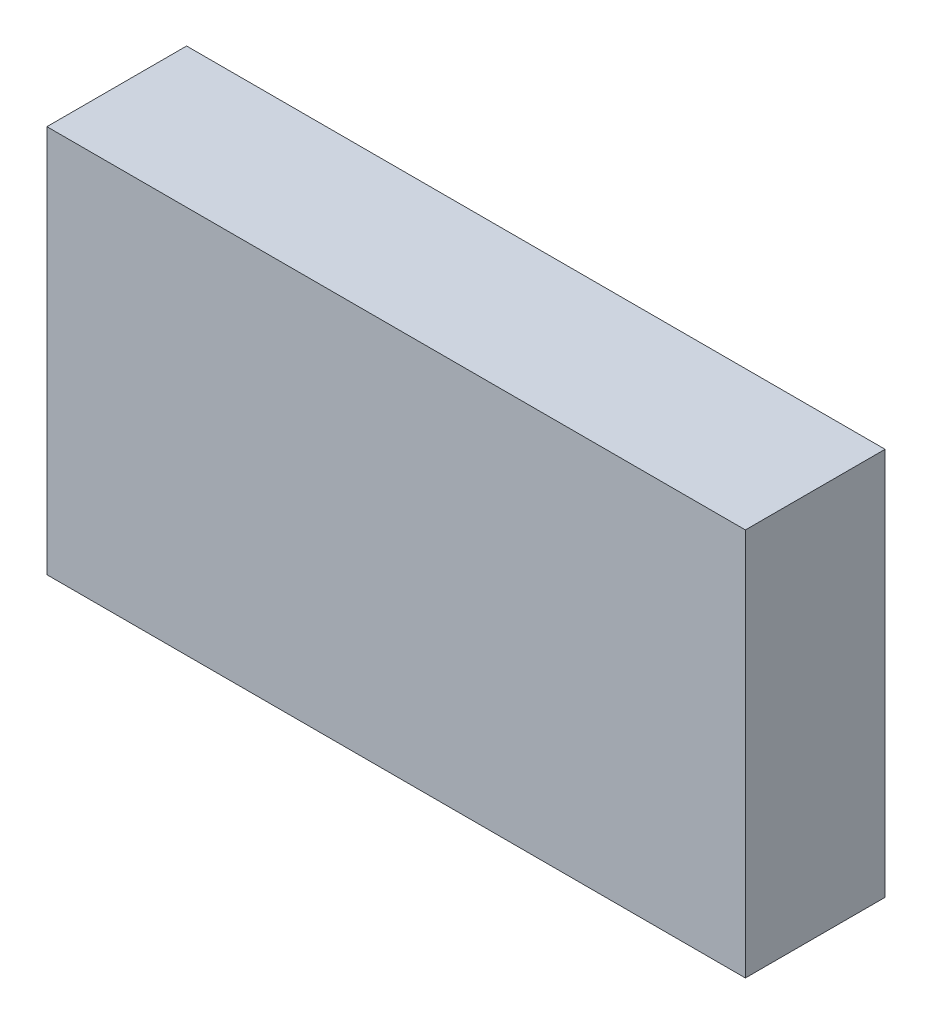
SolidWorks part; units mm, degrees
material "Plomb pur"
ref_plane "Front" through (0, 0, 0) normal (0, 0, 1) x (1, 0, 0)
ref_plane "Top" through (0, 0, 0) normal (0, 1, 0) x (1, 0, 0)
ref_plane "Right" through (0, 0, 0) normal (1, 0, 0) x (0, 0, -1)
sketch "Esquisse1" plane through (0, 0, 0) normal (0, 0, 1) x (1, 0, 0)
  line L1 (0, 0) -> (90, 0)
  line L2 (0, 0) -> (0, 50)
  line L3 (0, 50) -> (90, 50)
  line L4 (90, 0) -> (90, 50)
  dimension "D1" = 90
  dimension "D2" = 50
extrude "Boss.-Extru.1" add sketch "Esquisse1" along normal blind 18
